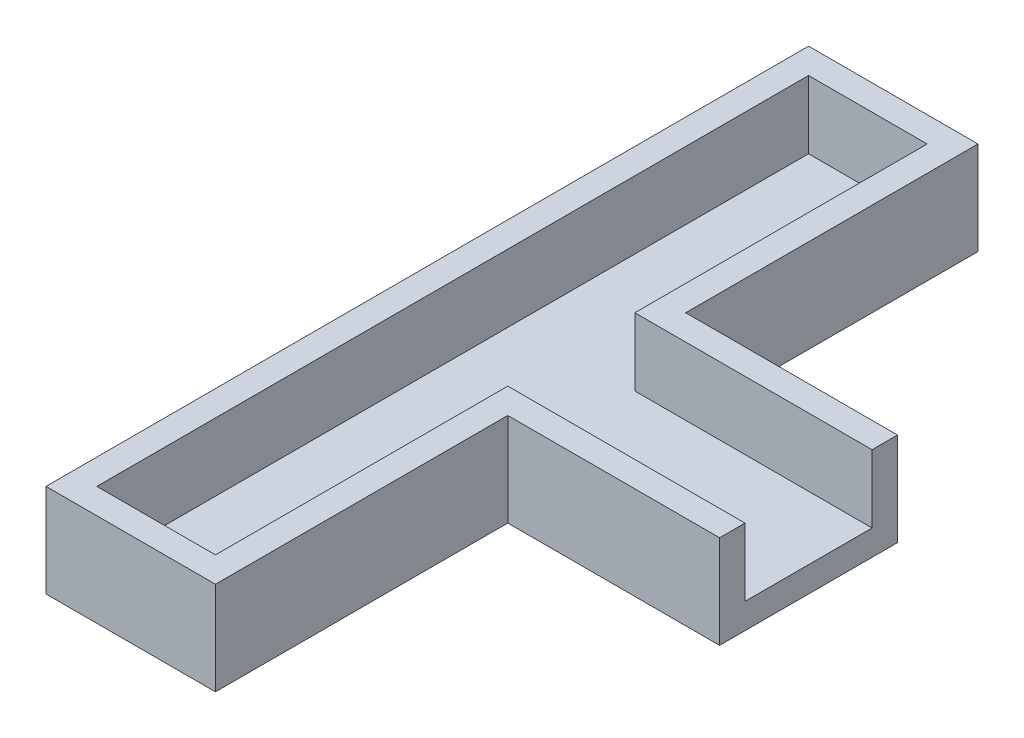
SolidWorks part; units mm, degrees
ref_plane "Front Plane" through (0, 0, 0) normal (0, 0, 1) x (1, 0, 0)
ref_plane "Top Plane" through (0, 0, 0) normal (0, 1, 0) x (1, 0, 0)
ref_plane "Right Plane" through (0, 0, 0) normal (1, 0, 0) x (0, 0, -1)
sketch "Sketch1" plane through (0, 0, 0) normal (0, 1, 0) x (1, 0, 0)
  line L1 (0, 0) -> (16, 0)
  line L2 (0, 0) -> (0, 72)
  line L3 (0, 72) -> (16, 72)
  line L4 (16, 0) -> (16, 72)
  dimension "D1" = 16
  dimension "D2" = 72
extrude "Boss-Extrude1" add sketch "Sketch1" along normal blind 2.4
sketch "Sketch2" plane through (0, 2.4, 0) normal (0, 1, 0) x (1, 0, 0)
  line L0 (2.4, 2.4) -> (2.4, 69.6)
  line L1 (0, 0) -> (16, 0)
  line L2 (0, 0) -> (0, 72)
  line L3 (0, 72) -> (16, 72)
  line L4 (16, 0) -> (16, 72)
  line L5 (2.4, 69.6) -> (13.6, 69.6)
  line L6 (13.6, 2.4) -> (13.6, 69.6)
  line L7 (2.4, 2.4) -> (13.6, 2.4)
  dimension "D1" = 2.4
extrude "Boss-Extrude2" add sketch "Sketch2" along normal blind 6.4
sketch "Sketch3" plane through (16, 0, 0) normal (1, 0, 0) x (0, 0, -1)
  line L0 (0, 8.8) -> (72, 8.8) construction
  line L1 (30, 8.8) -> (42, 8.8)
  line L2 (30, 8.8) -> (30, 2.4)
  line L3 (30, 2.4) -> (42, 2.4)
  line L4 (42, 8.8) -> (42, 2.4)
  line L5 (0, 0) -> (72, 0) construction
  point P6 (36, 8.8)
  point P9 (36, 0)
  dimension "D1" = 12
  dimension "D2" = 0
  dimension "D3" = 6.4
extrude "Cut-Extrude1" cut sketch "Sketch3" against normal blind 4.8
sketch "Sketch4" plane through (16, 0, 0) normal (1, 0, 0) x (0, 0, -1)
  line L0 (30, 2.4) -> (42, 2.4) construction
  line L1 (30, 8.8) -> (42, 8.8)
  line L2 (30, 8.8) -> (30, 2.4)
  line L3 (30, 2.4) -> (42, 2.4)
  line L4 (42, 8.8) -> (42, 2.4)
  line L5 (27.6, 8.8) -> (27.6, 0)
  line L6 (27.6, 0) -> (44.4, 0)
  line L7 (44.4, 8.8) -> (44.4, 0)
  line L9 (42, 8.8) -> (44.4, 8.8)
  line L10 (30.155, 8.8) -> (27.6, 8.8)
  line L11 (0, 8.8) -> (30, 8.8) construction
  line L12 (27.6, 11.2) -> (27.6, 0) construction
  line L13 (27.6, 11.2) -> (44.4, 11.2) construction
  line L14 (44.4, 11.2) -> (44.4, 0) construction
  line M1 (42, 2.4) -> (30, 2.4)
  line M2 (30, 2.4) -> (30, 8.8)
  line M3 (30, 8.8) -> (0, 8.8)
  line M5 (0, 0) -> (72, 0)
  line M7 (72, 8.8) -> (42, 8.8)
  line M8 (42, 8.8) -> (42, 2.4)
  dimension "D1" = 2.4
extrude "Boss-Extrude3" add sketch "Sketch4" along normal blind 20 contours L7 L5 M7 M8 M1 M2 M3 M5
equation "\"D3@Sketch3\"=\"D1@Boss-Extrude2\""
